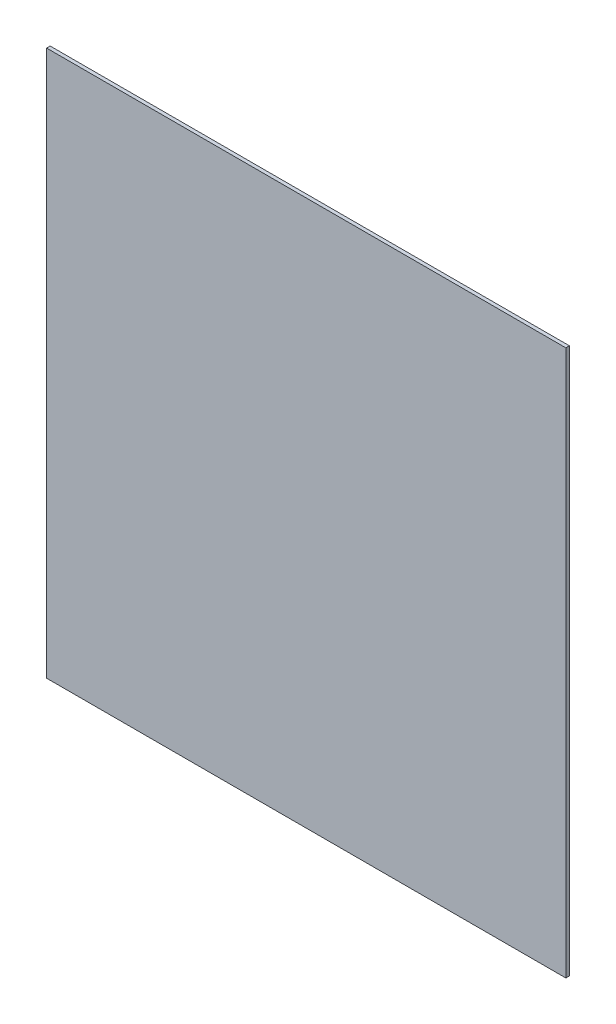
SolidWorks part; units mm, degrees
material "Perspex (TM) GS Acrylic Cast Sheet"
ref_plane "Front Plane" through (0, 0, 0) normal (0, 0, 1) x (1, 0, 0)
ref_plane "Top Plane" through (0, 0, 0) normal (0, 1, 0) x (1, 0, 0)
ref_plane "Right Plane" through (0, 0, 0) normal (1, 0, 0) x (0, 0, -1)
sketch "Sketch1" plane through (0, 0, 0) normal (0, 0, 1) x (1, 0, 0)
  line L1 (0, 0) -> (437.65, 0)
  line L2 (0, 0) -> (0, 460)
  line L3 (0, 460) -> (437.65, 460)
  line L4 (437.65, 0) -> (437.65, 460)
  dimension "D1" = 437.65
  dimension "D2" = 460
extrude "Boss-Extrude1" add sketch "Sketch1" along normal blind 3
